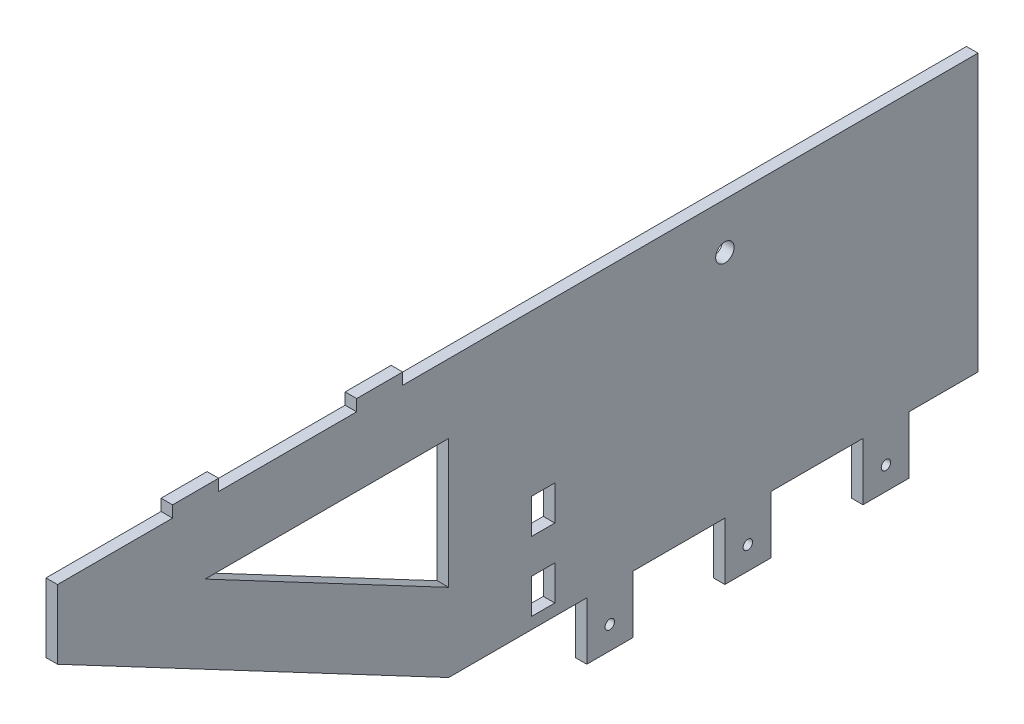
SolidWorks part; units mm, degrees
ref_plane "前基準面" through (0, 0, 0) normal (0, 0, 1) x (1, 0, 0)
ref_plane "上基準面" through (0, 0, 0) normal (0, 1, 0) x (1, 0, 0)
ref_plane "右基準面" through (0, 0, 0) normal (1, 0, 0) x (0, 0, -1)
sketch "草圖1" plane through (0, 0, 0) normal (1, 0, 0) x (0, 0, -1)
  line L1 (100, 60) -> (-100, 60)
  line L2 (100, 60) -> (100, -60)
  line L3 (100, -60) -> (-100, -60)
  line L4 (-100, 60) -> (-100, -60)
  line L5 (0, -60) -> (0, 60) construction
  line L6 (100, 0) -> (-100, 0) construction
  circle A0 centre (-10, 40) radius 4
  point P0 (0, 0)
  dimension "D3" = 8
  dimension "D1" = 200
  dimension "D2" = 120
  dimension "D4" = 100
  dimension "D5" = 90
extrude "填料-伸長1" add sketch "草圖1" along normal blind 5
sketch "草圖2" plane through (5, 0, 0) normal (1, 0, 0) x (0, 0, -1)
  line L0 (-100, -60) -> (100, -60) construction
  line L1 (-70, -60) -> (-50, -60)
  line L4 (-70, -60) -> (-70, -85)
  line L5 (-70, -85) -> (-50, -85)
  line L6 (-50, -85) -> (-50, -60)
  line L8 (-10, -60) -> (-10, -85)
  line L9 (-10, -85) -> (10, -85)
  line L10 (10, -85) -> (10, -60)
  line L12 (50, -60) -> (50, -85)
  line L13 (50, -85) -> (70, -85)
  line L14 (70, -85) -> (70, -60)
  line L17 (-100, 60) -> (-100, -60) construction
  line L18 (-70, -75) -> (70, -75) construction
  line L19 (-10, -60) -> (10, -60)
  line L20 (50, -60) -> (70, -60)
  line L21 (-70, -65) -> (70, -65) construction
  circle A0 centre (-60, -75) radius 2.05
  circle A1 centre (0, -75) radius 2.05
  circle A2 centre (60, -75) radius 2.05
  point P27 (-60, -85)
  point P30 (60, -85)
  point P32 (0, -60)
  dimension "D7" = 4.1
  dimension "D1" = 25
  dimension "D2" = 30
  dimension "D3" = 40
  dimension "D4" = 40
  dimension "D5" = 20
  dimension "D6" = 5
  dimension "D8" = 10
extrude "填料-伸長2" add sketch "草圖2" against normal blind 5
sketch "草圖3" plane through (5, 0, 0) normal (1, 0, 0) x (0, 0, -1)
  line L0 (-100, -60) -> (100, -60) construction
  line L1 (-100, 60) -> (-100, -60) construction
  line L2 (100, -60) -> (100, 60) construction
  line L4 (-100, 60) -> (-300, 60)
  line L5 (-300, 60) -> (-300, 30)
  line L6 (-300, 30) -> (-130, -60)
  line L7 (-130, -60) -> (-100, -60)
  line L8 (-100, 60) -> (-100, -60)
  line L9 (-130, 30) -> (-130, -26.0552)
  line L10 (-130, -26.0552) -> (-130, -26.0552)
  line L11 (-235.8821, 30) -> (-130, -26.0552)
  line L12 (-235.8821, 30) -> (-235.8821, 30)
  line L13 (-130, 30) -> (-235.8821, 30)
  line L14 (-100, -60) -> (-70, -60) construction
  dimension "D2" = 30
  dimension "D3" = 30
  dimension "D4" = 200
  dimension "D5" = 30
extrude "填料-伸長3" add sketch "草圖3" against normal blind 5
sketch "草圖4" plane through (5, 0, 0) normal (1, 0, 0) x (0, 0, -1)
  line L1 (-94, -9.8) -> (-83.9, -9.8)
  line L2 (-94, -9.8) -> (-94, -24.9)
  line L3 (-94, -24.9) -> (-83.9, -24.9)
  line L4 (-83.9, -9.8) -> (-83.9, -24.9)
  line L5 (-94, -39.9) -> (-83.9, -39.9)
  line L6 (-94, -39.9) -> (-94, -55)
  line L7 (-94, -55) -> (-83.9, -55)
  line L8 (-83.9, -39.9) -> (-83.9, -55)
  line L9 (-130, -26.0552) -> (-130, 30) construction
  line L10 (-130, -60) -> (-70, -60) construction
  dimension "D1" = 36
  dimension "D3" = 10.1
  dimension "D4" = 15
  dimension "D5" = 15.1
  dimension "D6" = 5
extrude "除料-伸長1" cut sketch "草圖4" against normal through all
sketch "草圖5" plane through (0, 60, 0) normal (0, 1, 0) x (1, 0, 0)
  line L0 (0, -130) -> (5, -130) construction
  line L1 (0, -130) -> (5, -130) construction
  line L2 (0, 100) -> (0, -300) construction
  line L3 (0, -150) -> (5, -150)
  line L4 (0, -150) -> (0, -170)
  line L5 (0, -170) -> (5, -170)
  line L6 (5, -150) -> (5, -170)
  line L7 (5, 100) -> (5, -300) construction
  line L9 (0, -230) -> (5, -230)
  line L10 (0, -230) -> (0, -250)
  line L11 (0, -250) -> (5, -250)
  line L12 (5, -230) -> (5, -250)
  dimension "D1" = 20
  dimension "D2" = 60
  dimension "D3" = 20
extrude "填料-伸長4" add sketch "草圖5" along normal blind 5
